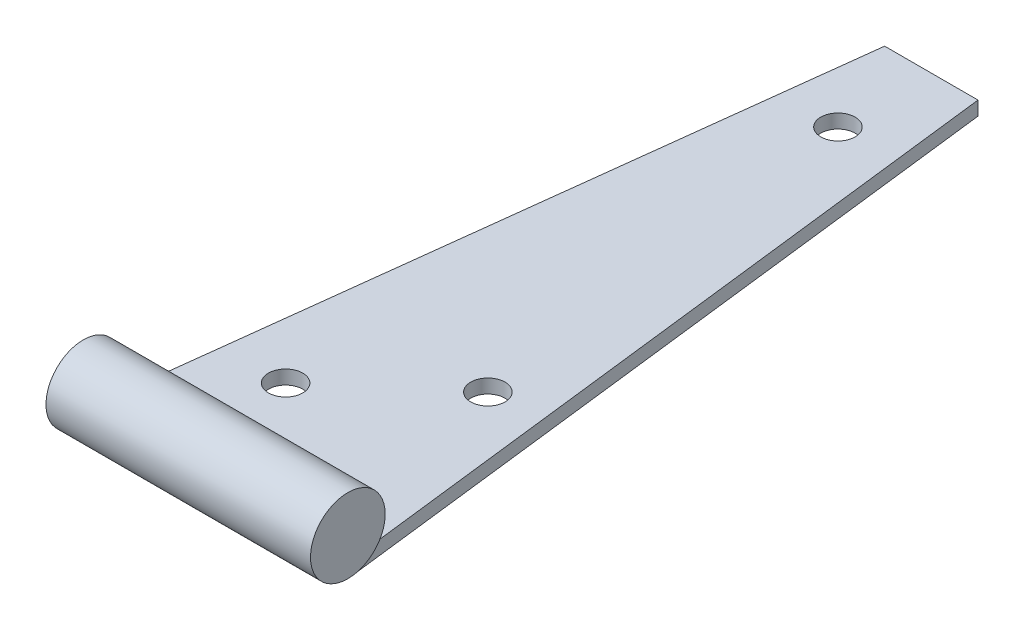
SolidWorks part; units mm, degrees
ref_plane "Front Plane" through (0, 0, 0) normal (0, 0, 1) x (1, 0, 0)
ref_plane "Top Plane" through (0, 0, 0) normal (0, 1, 0) x (1, 0, 0)
ref_plane "Right Plane" through (0, 0, 0) normal (1, 0, 0) x (0, 0, -1)
sketch "Sketch1" plane through (0, 0, 0) normal (0, 1, 0) x (1, 0, 0)
  line L0 (0, 0) -> (26.9875, 0)
  line L1 (13.4937, 0) -> (13.4937, 73.025) construction
  line L2 (18.2562, 73.025) -> (8.7312, 73.025)
  line L5 (0, 0) -> (8.7312, 73.025)
  line L6 (18.2562, 73.025) -> (26.9875, 0)
  point P8 (13.4937, 73.025)
extrude "Boss-Extrude1" add sketch "Sketch1" along normal blind 1.4224
sketch "Sketch2" plane through (0, 0, 0) normal (1, 0, 0) x (0, 0, -1)
  line L0 (0, 0) -> (0, 3.81) construction
  circle A0 centre (0, 3.81) radius 3.81
extrude "Boss-Extrude2" add sketch "Sketch2" along normal up to vertex
sketch "Sketch3" plane through (0, 1.4224, 0) normal (0, 1, 0) x (1, 0, 0)
  line L0 (13.4937, 73.025) -> (13.4937, -3.81) construction
  line L1 (18.2562, 73.025) -> (8.7312, 73.025) construction
  line L2 (0, -3.81) -> (26.9875, -3.81) construction
  line L3 (0, 0) -> (13.4937, 0) construction
  line L4 (13.4937, 0) -> (13.4938, 63.5) construction
  line L5 (13.4937, 0) -> (13.4938, 12.7) construction
  line L6 (13.4937, 0) -> (13.4938, 22.225) construction
  line L7 (13.4938, 12.7) -> (7.9375, 12.7) construction
  line L8 (13.4938, 22.225) -> (19.05, 22.225) construction
  circle A0 centre (13.4938, 63.5) radius 1.7526
  circle A1 centre (7.9375, 12.7) radius 1.7526
  circle A2 centre (19.05, 22.225) radius 1.7526
extrude "Cut-Extrude1" cut sketch "Sketch3" against normal blind 1.4224
